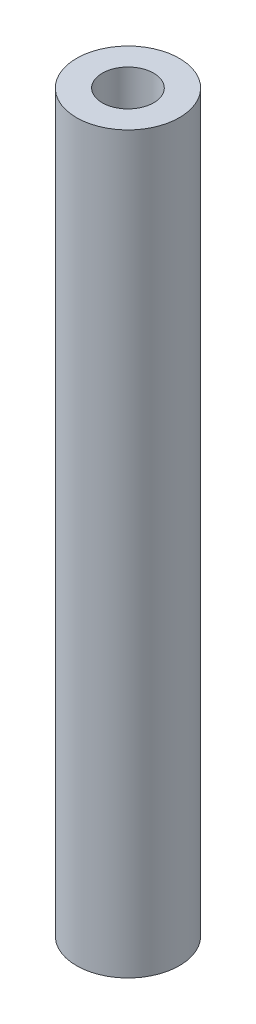
SolidWorks part; units mm, degrees
ref_plane "Front Plane" through (0, 0, 0) normal (0, 0, 1) x (1, 0, 0)
ref_plane "Top Plane" through (0, 0, 0) normal (0, 1, 0) x (1, 0, 0)
ref_plane "Right Plane" through (0, 0, 0) normal (1, 0, 0) x (0, 0, -1)
sketch "Sketch1" plane through (0, 0, 0) normal (0, 1, 0) x (1, 0, 0)
  circle A0 centre (0, 0) radius 3.5
  circle A1 centre (0, 0) radius 1.75
  dimension "D1" = 7
  dimension "D2" = 3.5
extrude "Boss-Extrude1" add sketch "Sketch1" along normal mid plane 50
